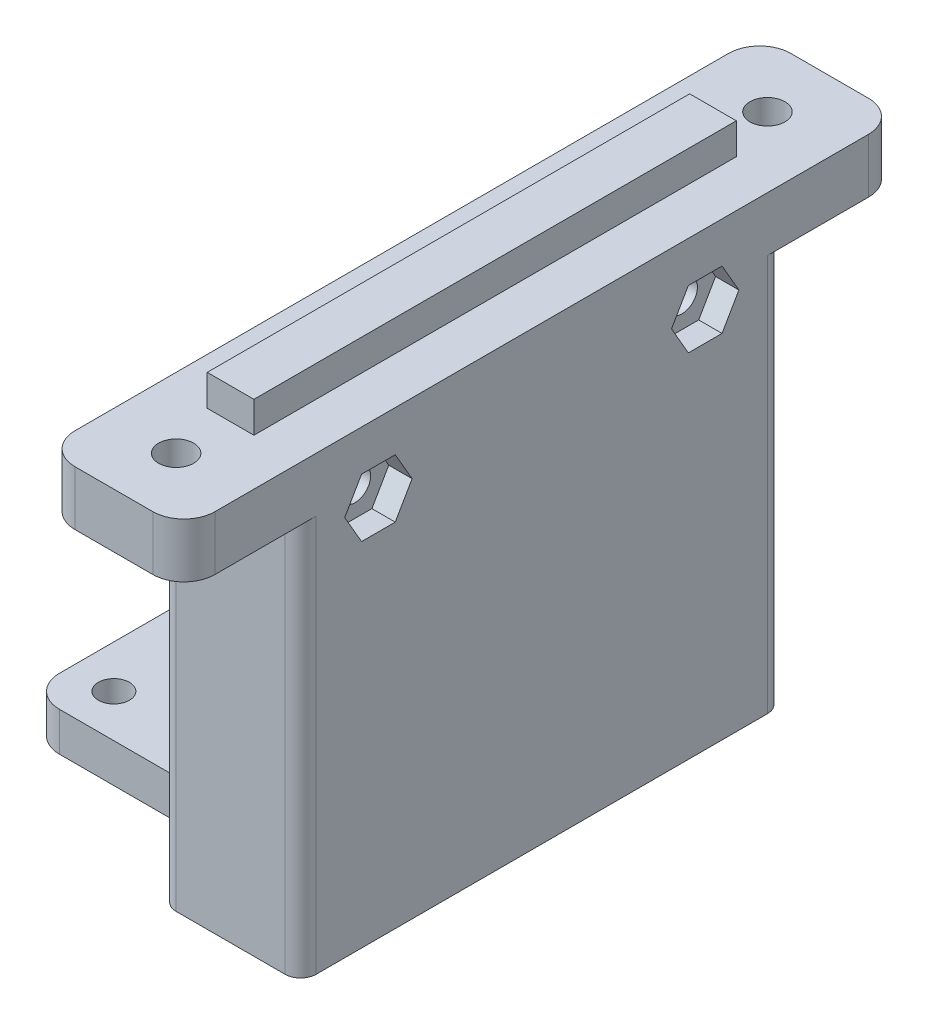
SolidWorks part; units mm, degrees
ref_plane "Спереди" through (0, 0, 0) normal (0, 0, 1) x (1, 0, 0)
ref_plane "Сверху" through (0, 0, 0) normal (0, 1, 0) x (1, 0, 0)
ref_plane "Справа" through (0, 0, 0) normal (1, 0, 0) x (0, 0, -1)
sketch "Эскиз1" plane through (0, 0, 0) normal (0, 1, 0) x (1, 0, 0)
  line L1 (0, 0) -> (45, 0)
  line L2 (0, 0) -> (0, 42)
  line L3 (0, 42) -> (45, 42)
  line L4 (45, 0) -> (45, 42)
  dimension "D1" = 45
  dimension "D2" = 42
extrude "Бобышка-Вытянуть1" add sketch "Эскиз1" along normal blind 5
sketch "Эскиз3" plane through (0, 0, 0) normal (0, -1, 0) x (1, 0, 0)
  line L0 (0, -42) -> (0, 0) construction
  line L1 (5.5, -5.5) -> (5.5, -36.5) construction
  line L2 (5.5, -36.5) -> (36.5, -36.5) construction
  line L3 (45, 0) -> (45, -42) construction
  circle A0 centre (21, -21) radius 14.775
  circle A1 centre (36.5, -5.5) radius 2
  circle A2 centre (5.5, -5.5) radius 2
  circle A3 centre (5.5, -36.5) radius 2
  circle A4 centre (36.5, -36.5) radius 2
  point P6 (21, -36.5)
  point P10 (5.5, -21)
  point P16 (0, -21)
  dimension "D1" = 29.55
  dimension "D3" = 4
  dimension "D2" = 24
  dimension "D4" = 31
  dimension "D5" = 31
extrude "Вырез-Вытянуть1" cut sketch "Эскиз3" against normal blind 13
sketch "Эскиз7" plane through (0, 0, 0) normal (0, 0, 1) x (1, 0, 0)
  line L0 (0, 0) -> (45, 0) construction
  line L1 (45, 5) -> (27, 5)
  line L2 (45, 5) -> (45, 0)
  line L3 (45, 0) -> (27, 0)
  line L4 (27, 5) -> (27, 0)
  dimension "D1" = 18
extrude "Бобышка-Вытянуть3" add sketch "Эскиз7" along normal blind 10
sketch "Эскиз8" plane through (0, 0, -42) normal (0, 0, -1) x (-1, 0, 0)
  line L0 (-45, 5) -> (0, 5) construction
  line L1 (-45, 0) -> (-27, 0)
  line L2 (-45, 0) -> (-45, 5)
  line L3 (-45, 5) -> (-27, 5)
  line L4 (-27, 0) -> (-27, 5)
  dimension "D1" = 18
extrude "Бобышка-Вытянуть4" add sketch "Эскиз8" along normal blind 10
sketch "Эскиз10" plane through (0, 5, 0) normal (0, 1, 0) x (1, 0, 0)
  line L0 (27, 52) -> (45, 52) construction
  line L1 (27, 52) -> (45, 52)
  line L2 (45, -10) -> (45, 52) construction
  line L3 (45, -10) -> (45, 52)
  line L4 (27, 52) -> (27, 42) construction
  line L5 (27, 52) -> (27, 42)
  line L6 (45, -10) -> (27, -10) construction
  line L7 (45, -10) -> (27, -10)
  line L8 (27, -10) -> (27, 0) construction
  line L9 (27, -10) -> (27, 0)
  line L10 (27, 42) -> (42, 42)
  line L11 (42, 42) -> (42, 0)
  line L12 (42, 0) -> (27, 0)
  circle A0 centre (36.5, 36.5) radius 2 construction
  dimension "D1" = 5.5
extrude "Бобышка-Вытянуть5" add sketch "Эскиз10" along normal blind 53
sketch "Эскиз11" plane through (0, 0, -52) normal (0, 0, -1) x (-1, 0, 0)
  line L0 (-27, 0) -> (-27, 58) construction
  line L1 (-45, 58) -> (-27, 58)
  line L2 (-45, 58) -> (-45, 51)
  line L3 (-45, 51) -> (-27, 51)
  line L4 (-27, 58) -> (-27, 51)
  dimension "D1" = 7
extrude "Бобышка-Вытянуть6" add sketch "Эскиз11" along normal blind 15 and the other way blind 77
sketch "Эскиз12" plane through (27, 0, 0) normal (-1, 0, 0) x (0, 0, 1)
  line L0 (-67, 58) -> (25, 58) construction
  line L1 (-49.5, 42) -> (7.5, 42)
  line L2 (-49.5, 42) -> (-49.5, 56)
  line L3 (-49.5, 56) -> (7.5, 56)
  line L4 (7.5, 42) -> (7.5, 56)
  line L5 (25, 58) -> (-67, 58) construction
  point P6 (-21, 56)
  point P9 (-21, 58)
  dimension "D1" = 14
  dimension "D2" = 2
  dimension "D3" = 57
extrude "Вырез-Вытянуть2" cut sketch "Эскиз12" against normal offset from surface (10 mm away) 8 contours L4 L3 L2 L1 up to face at (45, 40, -21)
sketch "Эскиз15" plane through (0, 58, 0) normal (0, 1, 0) x (1, 0, 0)
  line L0 (36, -17) -> (36, 59) construction
  line L1 (45, -25) -> (45, 67) construction
  line L2 (27, -25) -> (45, -25) construction
  line L3 (27, 67) -> (45, 67) construction
  line L4 (45, 67) -> (27, 67) construction
  circle A0 centre (36, -17) radius 2.25
  circle A1 centre (36, 59) radius 2.25
  point P4 (36, 21)
  point P7 (45, 21)
  point P14 (36, 67)
  dimension "D3" = 4.5
  dimension "D1" = 8
  dimension "D2" = 8
extrude "Вырез-Вытянуть5" cut sketch "Эскиз15" against normal blind 10
sketch "Эскиз16" plane through (0, 58, 0) normal (0, 1, 0) x (1, 0, 0)
  line L1 (39, -10) -> (33, -10)
  line L2 (39, -10) -> (39, 52)
  line L3 (39, 52) -> (33, 52)
  line L4 (33, -10) -> (33, 52)
  line L5 (27, -25) -> (45, -25) construction
  circle A0 centre (36, -17) radius 2.25 construction
  circle A1 centre (36, 59) radius 2.25 construction
  point P8 (36, -10)
  point P11 (36, -25)
  dimension "D2" = 7
  dimension "D1" = 6
  dimension "D3" = 7
extrude "Бобышка-Вытянуть7" add sketch "Эскиз16" along normal blind 4
sketch "Эскиз17" plane through (0, 0, -42) normal (0, 0, 1) x (1, 0, 0)
  line L0 (42, 51) -> (42, 5) construction
  line L1 (37, 42) -> (42, 42)
  line L2 (37, 42) -> (37, 51.7027)
  line L3 (37, 51.7027) -> (42, 51.7027)
  line L4 (42, 42) -> (42, 51.7027)
extrude "Бобышка-Вытянуть8" add sketch "Эскиз17" along normal blind 42
sketch "Эскиз13" plane through (45, 0, 0) normal (-1, 0, 0) x (0, 0, 1)
  line L0 (-49.5, 56) -> (-49.5, 42) construction
  line L1 (-42, 49) -> (0, 49) construction
  line L2 (7.5, 56) -> (-49.5, 56) construction
  circle A0 centre (-42, 49) radius 2
  circle A1 centre (0, 49) radius 2
  point P4 (-21, 49)
  point P8 (-49.5, 49)
  point P11 (-21, 56)
  dimension "D1" = 4
  dimension "D2" = 42
extrude "Вырез-Вытянуть3" cut sketch "Эскиз13" along normal blind 16
sketch "Эскиз14" plane through (45, 0, 0) normal (1, 0, 0) x (0, 0, -1)
  line L1 (2.1651, 52.75) -> (-2.1651, 52.75)
  line L2 (-2.1651, 52.75) -> (-4.3301, 49)
  line L3 (-4.3301, 49) -> (-2.1651, 45.25)
  line L4 (-2.1651, 45.25) -> (2.1651, 45.25)
  line L5 (2.1651, 45.25) -> (4.3301, 49)
  line L6 (4.3301, 49) -> (2.1651, 52.75)
  line L7 (44.1651, 52.75) -> (39.8349, 52.75)
  line L8 (39.8349, 52.75) -> (37.6699, 49)
  line L9 (37.6699, 49) -> (39.8349, 45.25)
  line L10 (39.8349, 45.25) -> (44.1651, 45.25)
  line L11 (44.1651, 45.25) -> (46.3301, 49)
  line L12 (46.3301, 49) -> (44.1651, 52.75)
  circle A0 centre (0, 49) radius 3.75 construction
  circle A1 centre (42, 49) radius 3.75 construction
  dimension "D1" = 7.5
extrude "Вырез-Вытянуть4" cut sketch "Эскиз14" against normal blind 3
fillet "Скругление1" radius 4 8 edges at (27, 23.5, 0) (27, 23.5, -42) (0, 2.5, 0) (0, 2.5, -42) (27, 54.5, -67) (45, 54.5, -67) (27, 54.5, 25) (45, 54.5, 25)
fillet "Скругление2" radius 2 4 edges at (45, 25.5, 10) (27, 25.5, 10) (45, 25.5, -52) (27, 25.5, -52)
